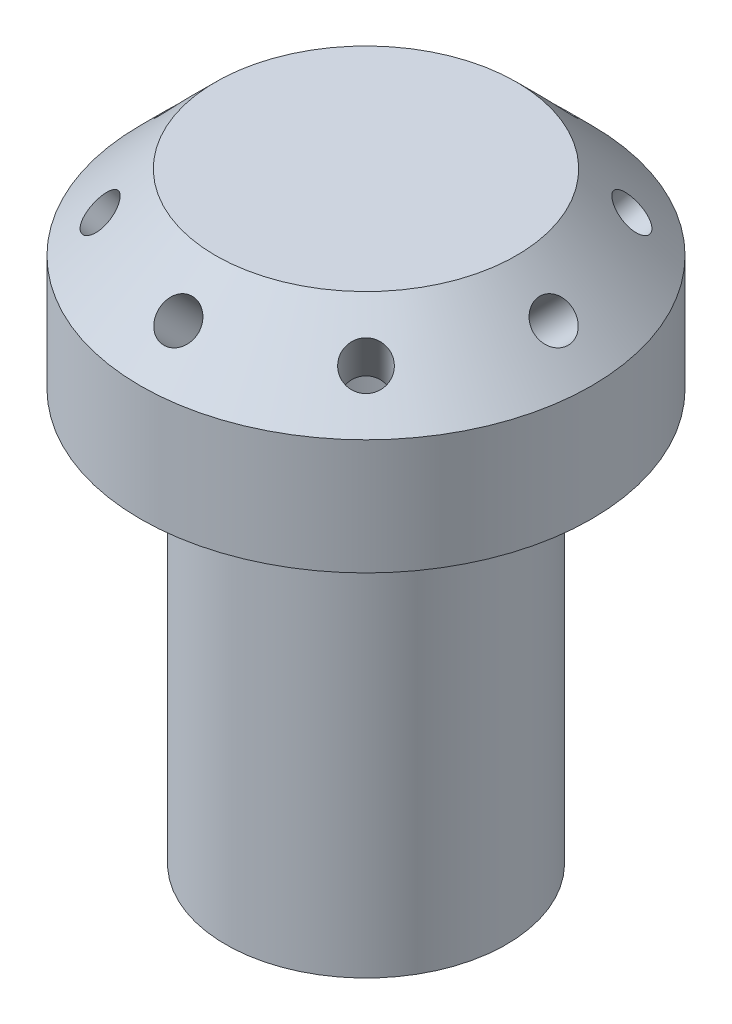
SolidWorks part; units mm, degrees
material "Plain Carbon Steel"
ref_plane "Front Plane" through (0, 0, 0) normal (0, 0, 1) x (1, 0, 0)
ref_plane "Top Plane" through (0, 0, 0) normal (0, 1, 0) x (1, 0, 0)
ref_plane "Right Plane" through (0, 0, 0) normal (1, 0, 0) x (0, 0, -1)
sketch "Sketch1" plane through (0, 0, 0) normal (0, 0, 1) x (1, 0, 0)
  line L0 (0, 0) -> (0, 76.2)
  line L1 (0, 76.2) -> (19.05, 76.2)
  line L2 (19.05, 76.2) -> (28.575, 66.675)
  line L3 (28.575, 66.675) -> (28.575, 52.07)
  line L4 (28.575, 52.07) -> (17.78, 52.07)
  line L5 (17.78, 52.07) -> (17.78, 0)
  line L6 (17.78, 0) -> (0, 0)
  line L7 (0, 0) -> (0, 112.8136) construction
  line L8 (12.7, 0) -> (12.7, 48.895)
  arc A0 (12.7, 48.895) -> (0, 61.595) centre (0, 48.895) ccw
  point P13 (0, 0)
  point P14 (0, 66.675)
  point P15 (1.8262, 59.6144)
  point P16 (0, 55.5462)
  point P17 (0, 64.6214)
  point P18 (0.4091, 61.1791)
  point P19 (0, 54.9203)
  point P20 (1.8262, 59.6144)
  dimension "D9" = 12.7
  dimension "D1" = 76.2
  dimension "D2" = 52.07
  dimension "D3" = 9.525
  dimension "D4" = 35.56
  dimension "D5" = 57.15
  dimension "D6" = 45
  dimension "D7" = 48.895
  dimension "D8" = 25.4
revolve "Revolve1" add sketch "Sketch1" angle 360 about L7
ref_plane "Plane1" through (47.625, 47.625, 0) normal (0.7071, 0.7071, 0) x (0.7071, -0.7071, 0)
sketch "Sketch3" plane through (47.625, 47.625, 0) normal (0.7071, 0.7071, 0) x (0.7071, -0.7071, 0)
  line L0 (0, 0) -> (-90.1435, 0) construction
  line L1 (-40.4112, 0) -> (-26.9408, 0) construction
  circle A0 centre (-33.676, 0) radius 2.54
  ellipse E0 centre (-53.8815, 0) end of major axis (-53.8815, -19.05) minor radius 13.4704 construction
  ellipse E1 centre (-53.8815, 0) end of major axis (-53.8815, -19.05) minor radius 13.4704 construction
  ellipse E2 centre (-47.1463, 0) end of major axis (-47.1463, -28.575) minor radius 20.2056 construction
  ellipse E3 centre (-47.1463, 0) end of major axis (-47.1463, -28.575) minor radius 20.2056 construction
  point P29 (0, 0)
  dimension "D1" = 5.08
extrude "Cut-Extrude1" cut sketch "Sketch3" against normal up to next
pattern_circular "CirPattern1" count 8 over 360 about axis through (0, 0, 0) along (0, -1, 0) of "Cut-Extrude1"
